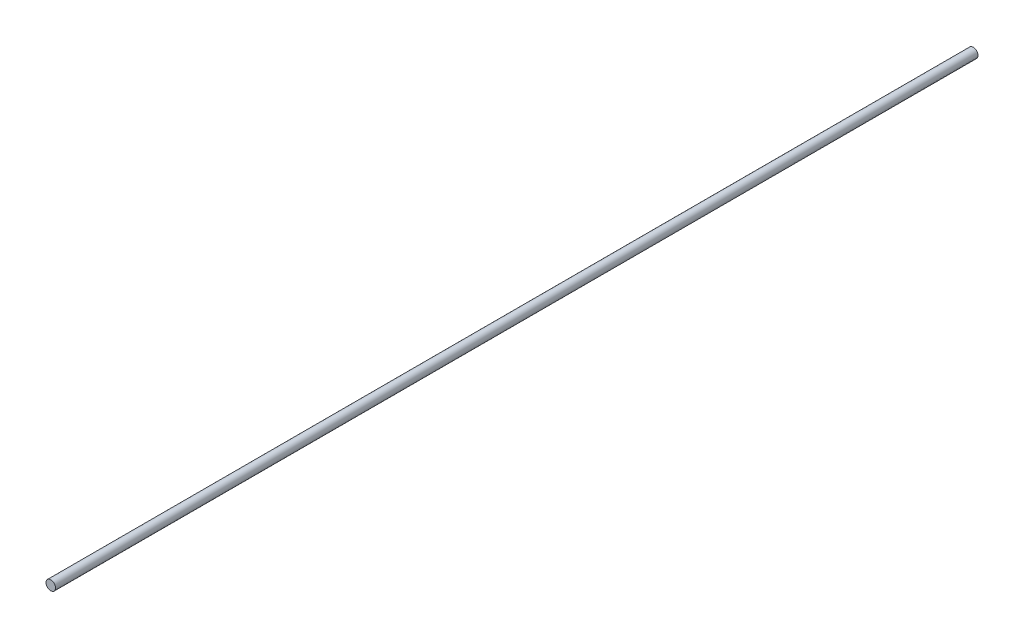
SolidWorks part; units mm, degrees
ref_plane "前视基准面" through (0, 0, 0) normal (0, 0, 1) x (1, 0, 0)
ref_plane "上视基准面" through (0, 0, 0) normal (0, 1, 0) x (1, 0, 0)
ref_plane "右视基准面" through (0, 0, 0) normal (1, 0, 0) x (0, 0, -1)
other "Configuration Table"
sketch "草图1" plane through (0, 0, 0) normal (0, 0, 1) x (1, 0, 0)
  circle A0 centre (0, 0) radius 0.4
extrude "D0p8钢索跨度_L77.3771" add sketch "草图1" along normal blind 77.3771
